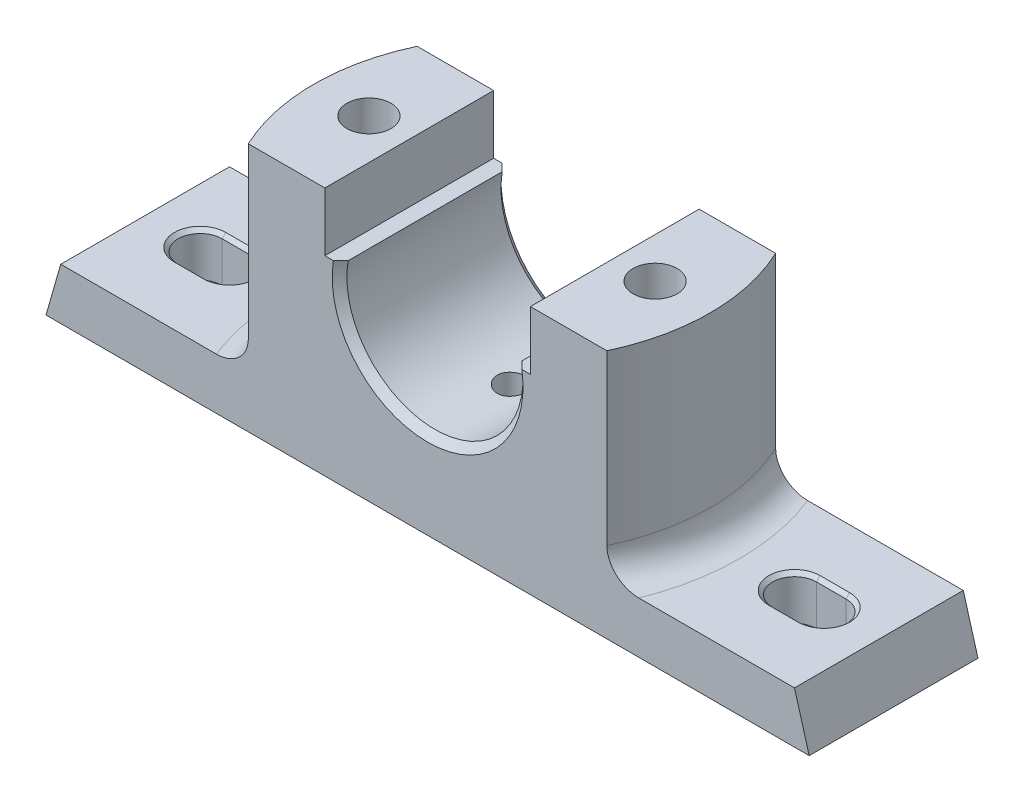
SolidWorks part; units mm, degrees
ref_plane "Front Plane" through (0, 0, 0) normal (0, 0, 1) x (1, 0, 0)
ref_plane "Top Plane" through (0, 0, 0) normal (0, 1, 0) x (1, 0, 0)
ref_plane "Right Plane" through (0, 0, 0) normal (1, 0, 0) x (0, 0, -1)
sketch "Sketch1" plane through (0, 0, 0) normal (0, 0, 1) x (1, 0, 0)
  line L0 (-104, 0) -> (104, 0)
  line L1 (104, 0) -> (99.9856, 14)
  line L2 (99.9856, 14) -> (-99.9856, 14)
  line L3 (-99.9856, 14) -> (-104, 0)
  point P6 (0, 0)
  dimension "D1" = 208
  dimension "D2" = 14
  dimension "D3" = 106
  dimension "D4" = 106
extrude "Boss-Extrude1" add sketch "Sketch1" along normal blind 46
sketch "Sketch2" plane through (0, 14, 0) normal (0, 1, 0) x (1, 0, 0)
  line L0 (0, 0) -> (0, -46) construction
  line L1 (99.9856, 0) -> (-99.9856, 0) construction
  line L2 (99.9856, -46) -> (-99.9856, -46) construction
  line L3 (-48.8569, 0) -> (48.8569, 0)
  line L4 (-48.8569, -46) -> (48.8569, -46)
  arc A0 (48.8569, 0) -> (48.8569, -46) centre (0, -23) cw
  arc A1 (-48.8569, 0) -> (-48.8569, -46) centre (0, -23) ccw
  dimension "D1" = 54
extrude "Boss-Extrude2" add sketch "Sketch2" along normal blind 54
sketch "Sketch3" plane through (0, 0, 46) normal (0, 0, 1) x (1, 0, 0)
  line L0 (0, 68) -> (0, 18.1073) construction
  line L1 (-48.8569, 68) -> (48.8569, 68) construction
  line L4 (28, 52) -> (28, 68)
  line L6 (28, 52) -> (23.6643, 52)
  line L7 (-28, 52) -> (-28, 68)
  line L8 (-28, 52) -> (-23.6643, 52)
  line L16 (-28, 68) -> (28, 68)
  arc A0 (-23.6643, 52) -> (23.6643, 52) centre (0, 48) ccw
  point P12 (0, 48)
  dimension "D1" = 48
  dimension "D2" = 20
  dimension "D3" = 56
  dimension "D4" = 16
extrude "Cut-Extrude1" cut sketch "Sketch3" against normal through all both and the other way through all
sketch "Sketch4" plane through (0, 14, 0) normal (0, 1, 0) x (1, 0, 0)
  line L0 (99.9856, -23) -> (28, -23)
  line L1 (99.9856, -46) -> (99.9856, 0) construction
  line L2 (28, 0) -> (28, -46) construction
  line L3 (77, -23) -> (85, -23) construction
  line L4 (77, -17) -> (85, -17)
  line L5 (77, -29) -> (85, -29)
  line L6 (0, 0) -> (0, -46) construction
  line L7 (-24, -46) -> (24, -46) construction
  line L8 (-77, -23) -> (-85, -23) construction
  line L9 (-77, -17) -> (-85, -17)
  line L10 (-77, -29) -> (-85, -29)
  arc A0 (77, -17) -> (77, -29) centre (77, -23) ccw
  arc A1 (85, -29) -> (85, -17) centre (85, -23) ccw
  arc A2 (-77, -17) -> (-77, -29) centre (-77, -23) cw
  arc A3 (-85, -29) -> (-85, -17) centre (-85, -23) cw
  point P8 (81, -23)
  point P20 (-81, -23)
  dimension "D1" = 6
  dimension "D2" = 8
  dimension "D3" = 77
extrude "Cut-Extrude2" cut sketch "Sketch4" against normal through all both contours A2 L10 A3 L9 | A1 L4 A0 L5
sketch "Sketch5" plane through (0, 68, 0) normal (0, 1, 0) x (1, 0, 0)
  line L0 (39, 0) -> (39, -46) construction
  line L3 (48.8569, 0) -> (28, 0) construction
  line L4 (28, -46) -> (48.8569, -46) construction
  dimension "D1" = 39
hole_wizard "Ø12.0mm Dowel Hole1" positions "Sketch7" profile "Sketch6" hole size "Ø12.0" standard "ANSI Metric" end condition through all
sketch "Sketch7" plane through (0, 68, 0) normal (0, 1, 0) x (1, 0, 0)
  line L0 (39, 0) -> (39, -46) construction
  point P0 (39, -23)
sketch "Sketch6" plane through (39, 68, 23) normal (1, 0, 0) x (0, 0, 1)
  line L0 (0, 0) -> (0, 68)
  line L1 (0, 68) -> (6, 68)
  line L2 (6, 68) -> (6, 0)
  line L5 (6, 0) -> (0, 0)
  line L11 (0, -6.35) -> (0, 107.95) construction
  dimension "Thru Hole Dia." = 12
  dimension "Thru Hole Depth" = 68
mirror "Mirror1" about plane through (0, 0, 0) normal (1, 0, 0) of "Ø12.0mm Dowel Hole1"
ref_plane "Plane1" through (0, 24, 0) normal (0, 1, 0) x (1, 0, 0)
sketch "Sketch14" plane through (0, 0, 0) normal (0, -1, 0) x (1, 0, 0)
  line L0 (0, 46) -> (0, 63.7772)
  line L1 (-53, 37) -> (-25, 37)
  line L2 (-53, 37) -> (-53, 9)
  line L3 (-53, 9) -> (-25, 9)
  line L4 (-25, 37) -> (-25, 9)
  line L5 (-53, 37) -> (-25, 9) construction
  line L6 (-53, 9) -> (-25, 37) construction
  line L7 (-104, 46) -> (104, 46) construction
  line L8 (53, 9) -> (25, 9)
  line L9 (25, 37) -> (25, 9)
  line L10 (53, 37) -> (25, 37)
  line L11 (53, 37) -> (53, 9)
  point P0 (-39, 23)
  circle M12 centre (-39, 23) radius 6
  circle M13 centre (39, 23) radius 6
  dimension "D1" = 28
extrude "Cut-Extrude5" cut sketch "Sketch14" against normal blind 10 contours L4 L1 L2 L3 M12 | L11 L10 L9 L8 M13
ref_plane "Plane2" through (0, 68, 0) normal (0, 1, 0) x (1, 0, 0)
sketch "Sketch15" plane through (0, 68, 0) normal (0, 1, 0) x (1, 0, 0)
  line L0 (0, 0) -> (0, -46)
  line L1 (-24, -46) -> (24, -46) construction
  circle A0 centre (0, -23) radius 4
  dimension "D1" = 8
extrude "Cut-Extrude6" cut sketch "Sketch15" against normal blind 54 contours A0
ref_plane "Plane3" through (0, 0, 23) normal (0, 0, 1) x (1, 0, 0)
sketch "Sketch18" plane through (0, 0, 23) normal (0, 0, 1) x (1, 0, 0)
  line L0 (0, 0) -> (-97.5, 0)
  line L1 (-104, 0) -> (104, 0) construction
  line L2 (-97.5, 0) -> (-96.9265, 2)
  line L3 (-96.9265, 2) -> (96.9265, 2)
  line L4 (0, 2) -> (0, 14.8023)
  line L5 (97.5, 0) -> (96.9265, 2)
  line L6 (-97.5, 0) -> (97.5, 0)
  line L7 (-99.9856, 14) -> (-104, 0) construction
  line L8 (104, 0) -> (99.9856, 14) construction
  dimension "D1" = 2
  dimension "D2" = 195
extrude "Cut-Extrude7" cut sketch "Sketch18" against normal mid plane 42 contours L6 L5 L3 L2
chamfer "Chamfer2" distance 2 angle 45 2 edges at (0, 24, 46) (0, 24, 0)
fillet "Fillet1" radius 8 2 edges at (-54, 14, 23) (54, 14, 23)
chamfer "Chamfer3" distance 1 angle 45 8 edges at (81, 14, 29) (71, 14, 23) (91, 14, 23) (81, 14, 17) (-91, 14, 23) (-81, 14, 17) (-81, 14, 29) (-71, 14, 23)
